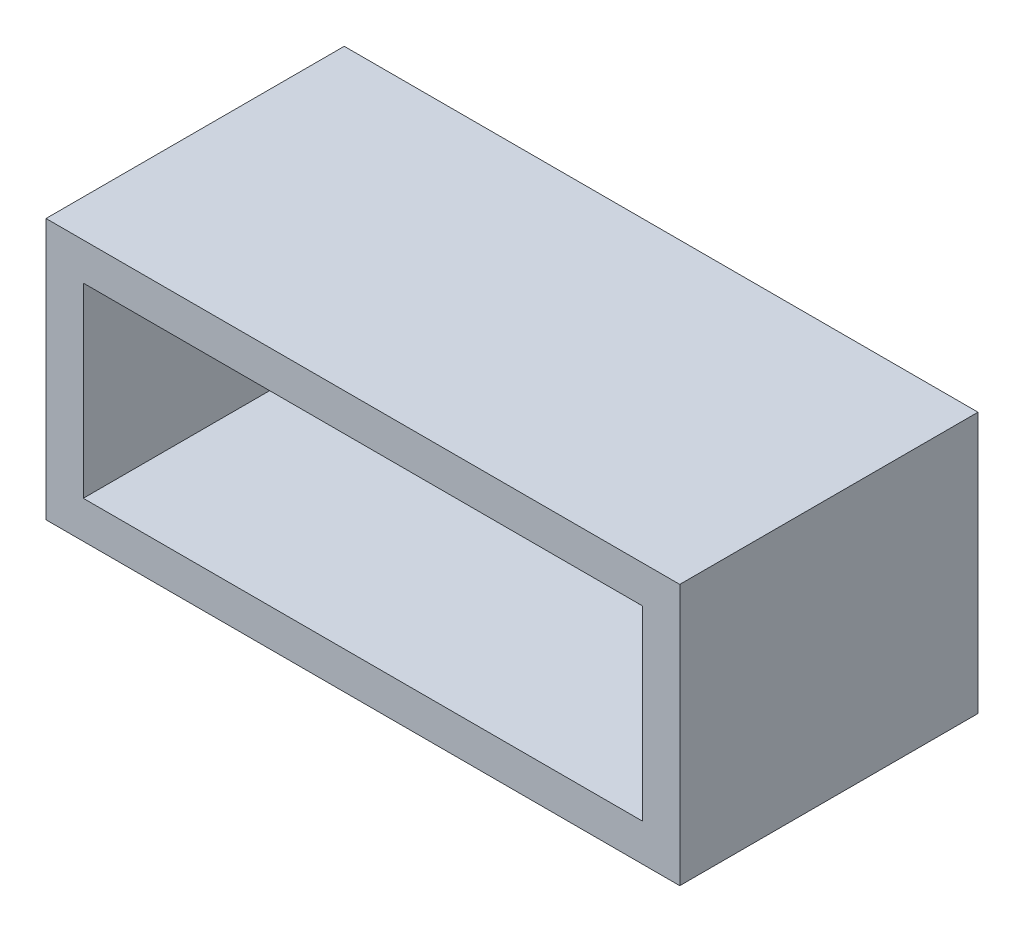
SolidWorks part; units mm, degrees
ref_plane "Front Plane" through (0, 0, 0) normal (0, 0, 1) x (1, 0, 0)
ref_plane "Top Plane" through (0, 0, 0) normal (0, 1, 0) x (1, 0, 0)
ref_plane "Right Plane" through (0, 0, 0) normal (1, 0, 0) x (0, 0, -1)
sketch "Sketch1" plane through (0, 0, 0) normal (0, 0, 1) x (1, 0, 0)
  line L0 (-75, 25) -> (75, 25)
  line L1 (-85, -35) -> (85, -35)
  line L2 (-85, -35) -> (-85, 35)
  line L3 (-85, 35) -> (85, 35)
  line L4 (85, -35) -> (85, 35)
  line L5 (-85, -35) -> (85, 35) construction
  line L6 (-85, 35) -> (85, -35) construction
  line L7 (75, -25) -> (75, 25)
  line L8 (-75, -25) -> (75, -25)
  line L9 (-75, -25) -> (-75, 25)
  point P0 (0, 0)
  dimension "D1" = 170
  dimension "D2" = 70
  dimension "D3" = 10
extrude "Boss-Extrude1" add sketch "Sketch1" along normal blind 80
sketch "Sketch2" plane through (75, 0, 0) normal (-1, 0, 0) x (0, 0, 1)
  line L5 (0, 25) -> (10, 25)
  line L6 (0, 25) -> (0, 12)
  line L7 (0, 12) -> (10, 12)
  line L8 (10, 25) -> (10, 12)
  dimension "D1" = 13
  dimension "D2" = 10
extrude "Boss-Extrude2" add sketch "Sketch2" along normal blind 15
sketch "Sketch3" plane through (0, 0, 0) normal (0, 0, -1) x (-1, 0, 0)
  circle A0 centre (-69.4311, 20.0599) radius 2.3815
extrude "Cut-Extrude1" cut sketch "Sketch3" against normal blind 15
ref_plane "Plane1" through (0, 0, 0) normal (1, 0, 0) x (0, 0, -1)
mirror "Mirror1" about plane through (0, 0, 0) normal (1, 0, 0) of "Cut-Extrude1", "Boss-Extrude2"
